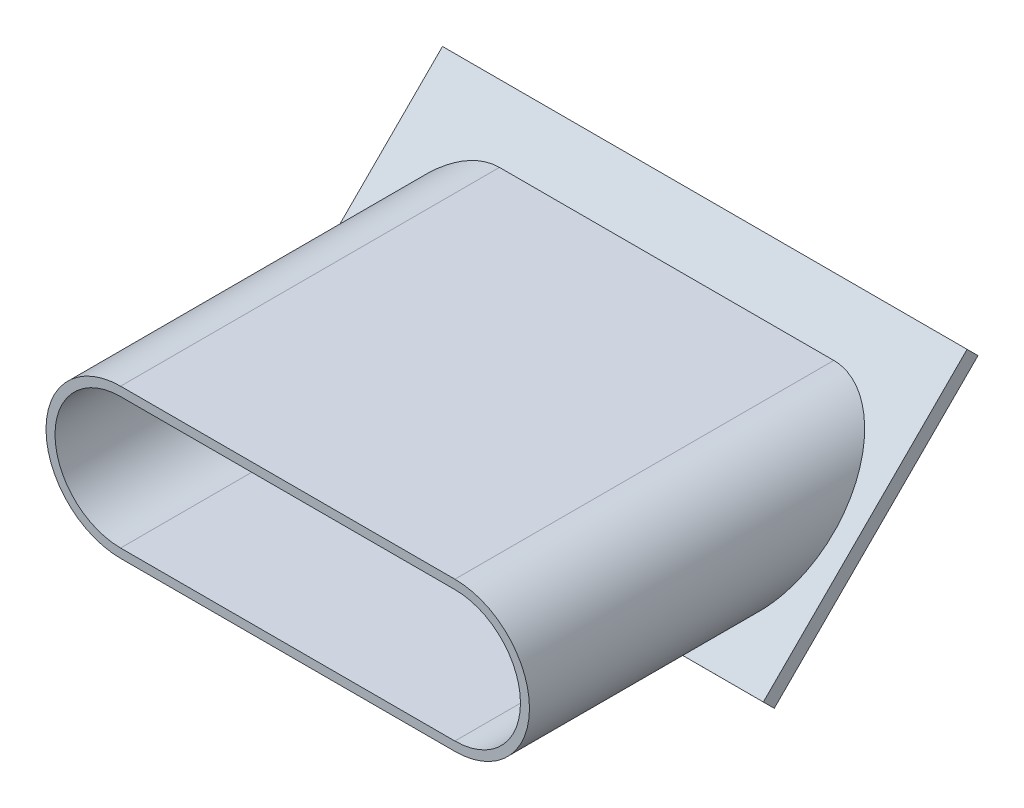
SolidWorks part; units mm, degrees
ref_plane "Front Plane" through (0, 0, 0) normal (0, 0, 1) x (1, 0, 0)
ref_plane "Top Plane" through (0, 0, 0) normal (0, 1, 0) x (1, 0, 0)
ref_plane "Right Plane" through (0, 0, 0) normal (1, 0, 0) x (0, 0, -1)
sketch "Sketch22" plane through (0, 0, 0) normal (0, 0, 1) x (1, 0, 0)
  line L3 (32.5, 0) -> (-32.5, 0) construction
  line L10 (32.5, -14.5) -> (-32.5, -14.5)
  line L11 (32.5, 14.5) -> (-32.5, 14.5)
  arc A2 (32.5, -14.5) -> (32.5, 14.5) centre (32.5, 0) ccw
  arc A3 (-32.5, 14.5) -> (-32.5, -14.5) centre (-32.5, 0) ccw
  point P8 (0, 0)
  point P15 (0, 0)
extrude "Boss-Extrude12" add sketch "Sketch22" along normal blind 80
sketch "Sketch34" plane through (0, 0, 0) normal (0, 0, -1) x (-1, 0, 0)
  line L0 (32.5, -14.5) -> (32.5, 14.5) construction
ref_plane "Plane5" through (-32.5, 0, 0) normal (1, 0, 0) x (0, 0, -1)
sketch "Sketch35" plane through (-32.5, 0, 0) normal (1, 0, 0) x (0, 0, -1)
  line L0 (0, 14.5) -> (-29.0269, -14.5)
  line L1 (-80, -14.5) -> (0, -14.5) construction
  line L2 (-29.0269, -14.5) -> (0, -14.5)
  line L3 (0, -14.5) -> (0, 14.5)
extrude "Cut-Extrude10" cut sketch "Sketch35" against normal through all and the other way through all
ref_plane "Plane6" through (0, 7.2567, 7.25) normal (0, -0.7074, -0.7068) x (-1, 0, 0)
sketch "Sketch37" plane through (0, 7.2567, 7.25) normal (0, -0.7074, -0.7068) x (-1, 0, 0)
  line L0 (0, 10.2483) -> (0, -30.7829) construction
  line L1 (-32.5, 10.2483) -> (32.5, 10.2483) construction
  line L2 (32.5, -30.7829) -> (-32.5, -30.7829) construction
  line L4 (51, 17.7327) -> (-51, 17.7327)
  line L5 (51, 17.7327) -> (51, -38.2673)
  line L6 (51, -38.2673) -> (-51, -38.2673)
  line L7 (-51, 17.7327) -> (-51, -38.2673)
  line L8 (51, 17.7327) -> (-51, -38.2673) construction
  line L9 (51, -38.2673) -> (-51, 17.7327) construction
  point P6 (0, -10.2673)
extrude "Boss-Extrude16" add sketch "Sketch37" against normal blind 3
sketch "Sketch38" plane through (0, 0, 80) normal (0, 0, 1) x (1, 0, 0)
  line L0 (32.5, -14.5) -> (32.5, 14.5)
  line L1 (-32.5, 0) -> (32.5, 0) construction
  line L2 (-32.5, 12.75) -> (32.5, 12.75)
  line L3 (-32.5, -12.75) -> (32.5, -12.75)
  arc A0 (-32.5, 12.75) -> (-32.5, -12.75) centre (-32.5, 0) ccw
  arc A1 (32.5, -12.75) -> (32.5, 12.75) centre (32.5, 0) ccw
  point P6 (0, 0)
extrude "Cut-Extrude11" cut sketch "Sketch38" against normal through all contours L3 A1 L2 A0
sketch "Sketch40" plane through (0, -12.75, 0) normal (0, 1, 0) x (1, 0, 0)
  line L0 (32.5, -27.2752) -> (32.5, -77.9154) construction
  line L1 (32.5, -27.2752) -> (32.5, -80) construction
  line L2 (-32.5, -27.2752) -> (-32.5, -77.9154) construction
  line L3 (-32.5, -27.2752) -> (-32.5, -80) construction
  line L4 (-32.5, -77.9154) -> (32.5, -77.9154) construction
  line L6 (69.7281, -77.9154) -> (-57.7587, -77.9154)
  line L7 (-57.7587, -77.9154) -> (-57.7587, -89.8582)
  line L8 (-57.7587, -89.8582) -> (69.7281, -89.8582)
  line L9 (69.7281, -89.8582) -> (69.7281, -77.9154)
extrude "Cut-Extrude12" cut sketch "Sketch40" along normal through all and the other way up to surface other way up to face at (0, -14.5, 56.6357)
sketch "Sketch42" plane through (-51, 0, 0) normal (-1, 0, 0) x (0, 0, 1)
  line L0 (77.9154, 14.5) -> (27.025, 14.5)
  line L1 (77.9154, 14.5) -> (4.2446, 14.5) construction
  line L2 (27.025, 14.5) -> (27.025, -8.2593)
  line L3 (36.4419, -17.6675) -> (-3.1744, 21.9121) construction
  line L4 (27.025, -8.2593) -> (33.2715, -14.5)
  line L5 (33.2715, -14.5) -> (77.9154, -14.5)
  line L6 (77.9154, -14.5) -> (77.9154, 14.5)
sketch "Sketch43" plane through (0, 12.75, 0) normal (0, -1, 0) x (-1, 0, 0)
  line L0 (0, -1.7516) -> (0, -77.9154)
  line L1 (32.5, -1.7516) -> (-32.5, -1.7516) construction
  line L2 (-32.5, -77.9154) -> (32.5, -77.9154) construction
